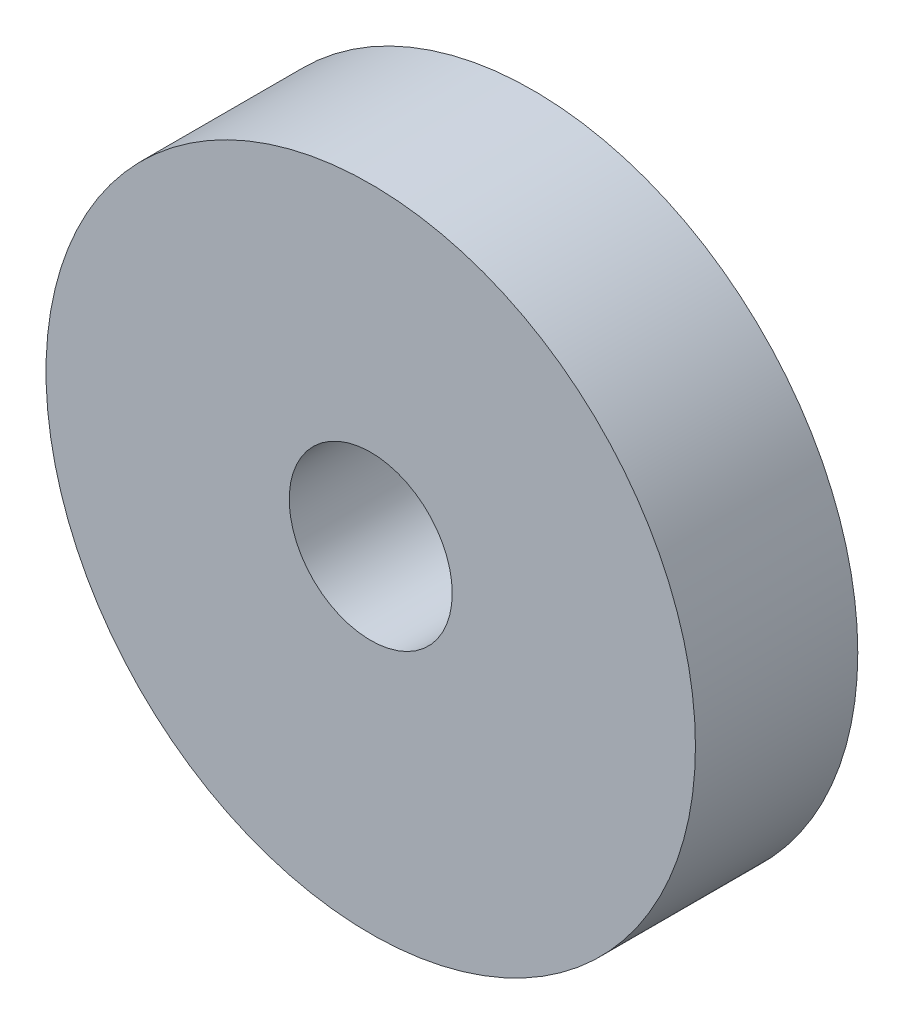
SolidWorks part; units mm, degrees
ref_plane "Front Plane" through (0, 0, 0) normal (0, 0, 1) x (1, 0, 0)
ref_plane "Top Plane" through (0, 0, 0) normal (0, 1, 0) x (1, 0, 0)
ref_plane "Right Plane" through (0, 0, 0) normal (1, 0, 0) x (0, 0, -1)
sketch "Sketch1" plane through (0, 0, 0) normal (0, 0, 1) x (1, 0, 0)
  circle A0 centre (0, 0) radius 10
  circle A1 centre (0, 0.3363) radius 2.51
  dimension "D1" = 20
  dimension "D2" = 5.02
extrude "Boss-Extrude1" add sketch "Sketch1" along normal blind 5
